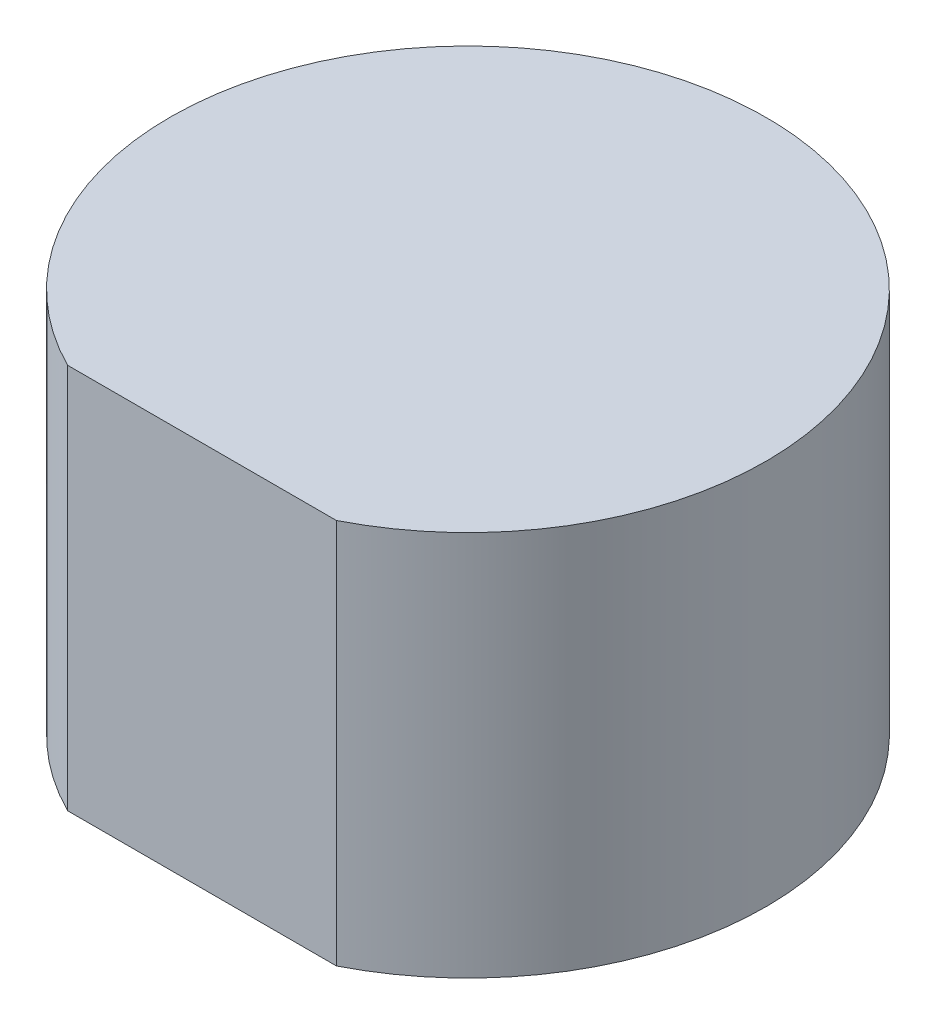
SolidWorks part; units mm, degrees
material "PA Type 6"
ref_plane "Front Plane" through (0, 0, 0) normal (0, 0, 1) x (1, 0, 0)
ref_plane "Top Plane" through (0, 0, 0) normal (0, 1, 0) x (1, 0, 0)
ref_plane "Right Plane" through (0, 0, 0) normal (1, 0, 0) x (0, 0, -1)
sketch "Sketch1" plane through (0, 0, 0) normal (0, 1, 0) x (1, 0, 0)
  line L0 (0, 0) -> (11.5, 0) construction
  line L1 (0, 0) -> (-11.5, 0) construction
  line L2 (-11.5, 0) -> (-11.5, -45.5373) construction
  line L3 (11.5, 0) -> (11.5, -46.5905) construction
  line L4 (11.5, -22.7484) -> (-11.5, -22.7484)
  arc A0 (11.5, -22.7484) -> (-11.5, -22.7484) centre (0, 0) ccw
  dimension "D1" = 11.5
  dimension "D2" = 11.5
  dimension "D3" = 50.98
extrude "Boss-Extrude1" add sketch "Sketch1" along normal blind 33
